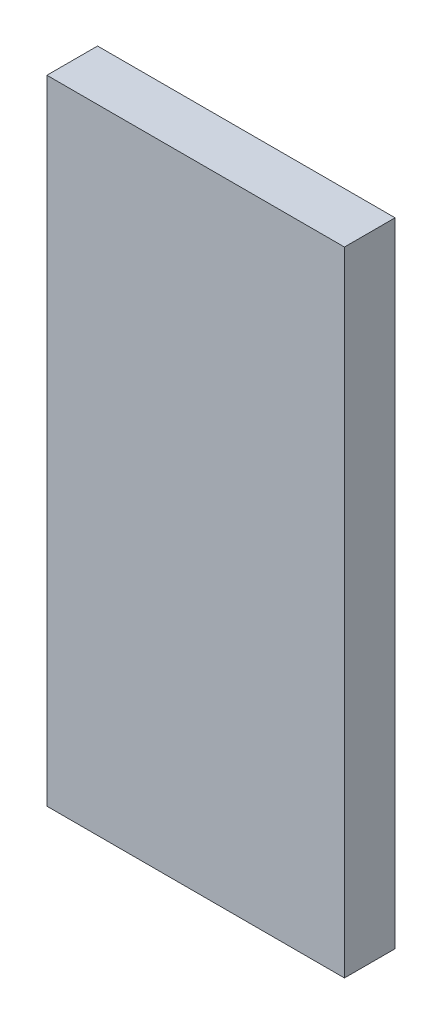
SolidWorks part; units mm, degrees
material "Q235A"
ref_plane "前视" through (0, 0, 0) normal (0, 0, 1) x (1, 0, 0)
ref_plane "上视" through (0, 0, 0) normal (0, 1, 0) x (1, 0, 0)
ref_plane "右视" through (0, 0, 0) normal (1, 0, 0) x (0, 0, -1)
sketch "草图1" plane through (0, 0, 0) normal (0, 0, 1) x (1, 0, 0)
  line L1 (47, -100) -> (-47, -100)
  line L2 (47, -100) -> (47, 100)
  line L3 (47, 100) -> (-47, 100)
  line L4 (-47, -100) -> (-47, 100)
  line L5 (47, -100) -> (-47, 100) construction
  line L6 (47, 100) -> (-47, -100) construction
  point P0 (0, 0)
  dimension "D1" = 200
  dimension "D2" = 94
extrude "凸台-拉伸1" add sketch "草图1" along normal blind 16
